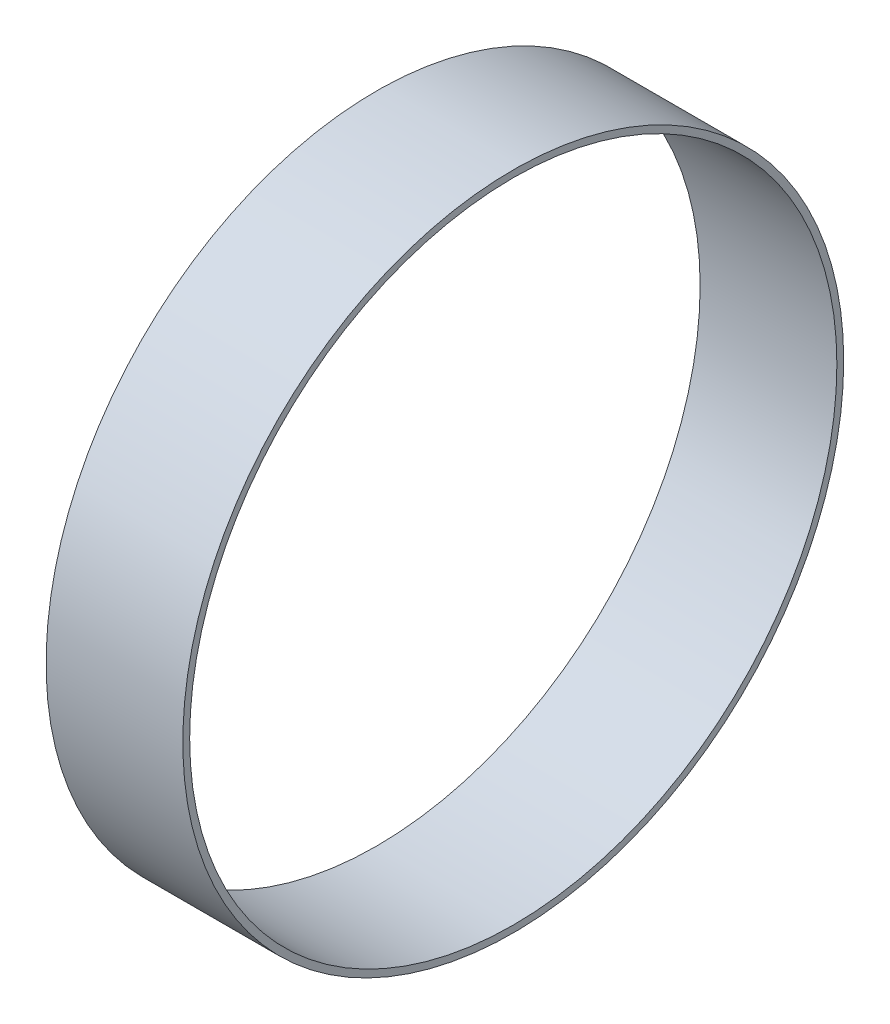
SolidWorks part; units mm, degrees
ref_plane "Front Plane" through (0, 0, 0) normal (0, 0, 1) x (1, 0, 0)
ref_plane "Top Plane" through (0, 0, 0) normal (0, 1, 0) x (1, 0, 0)
ref_plane "Right Plane" through (0, 0, 0) normal (1, 0, 0) x (0, 0, -1)
sketch "Sketch1" plane through (0, 0, 0) normal (1, 0, 0) x (0, 0, -1)
  circle A0 centre (0, 0) radius 71
  circle A1 centre (0, 0) radius 72.5
  dimension "D1" = 142
  dimension "D2" = 145
extrude "Boss-Extrude1" add sketch "Sketch1" along normal blind 30
